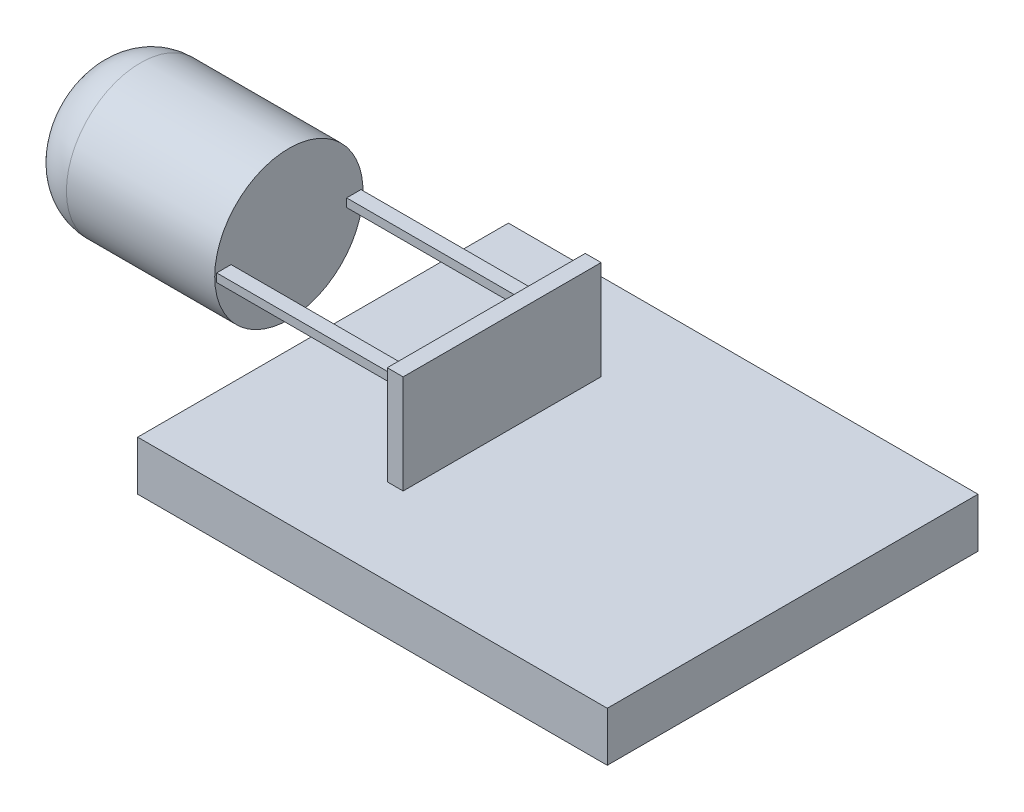
SolidWorks part; units mm, degrees
ref_plane "Plan de face" through (0, 0, 0) normal (0, 0, 1) x (1, 0, 0)
ref_plane "Plan de dessus" through (0, 0, 0) normal (0, 1, 0) x (1, 0, 0)
ref_plane "Plan de droite" through (0, 0, 0) normal (1, 0, 0) x (0, 0, -1)
sketch "Esquisse1" plane through (0, 0, 0) normal (0, 1, 0) x (1, 0, 0)
  line L1 (-9.5, 7.5) -> (9.5, 7.5)
  line L2 (-9.5, 7.5) -> (-9.5, -7.5)
  line L3 (-9.5, -7.5) -> (9.5, -7.5)
  line L4 (9.5, 7.5) -> (9.5, -7.5)
  line L5 (-9.5, 7.5) -> (9.5, -7.5) construction
  line L6 (-9.5, -7.5) -> (9.5, 7.5) construction
  point P0 (0, 0)
  dimension "D1" = 15
  dimension "D2" = 19
extrude "Boss.-Extru.1" add sketch "Esquisse1" along normal blind 2
sketch "Esquisse2" plane through (0, 2, 0) normal (0, 1, 0) x (1, 0, 0)
  line L1 (-2.8834, -4.0184) -> (-2.2409, -4.0184)
  line L2 (-2.8834, -4.0184) -> (-2.8834, 3.9928)
  line L3 (-2.8834, 3.9928) -> (-2.2409, 3.9928)
  line L4 (-2.2409, -4.0184) -> (-2.2409, 3.9928)
extrude "Boss.-Extru.2" add sketch "Esquisse2" along normal blind 4
sketch "Esquisse3" plane through (-2.8834, 0, 0) normal (-1, 0, 0) x (0, 0, 1)
  line L1 (-2.9186, 4.7729) -> (-2.3381, 4.7729)
  line L2 (-2.9186, 4.7729) -> (-2.9186, 4.4343)
  line L3 (-2.9186, 4.4343) -> (-2.3381, 4.4343)
  line L4 (-2.3381, 4.7729) -> (-2.3381, 4.4343)
extrude "Boss.-Extru.3" add sketch "Esquisse3" along normal blind 8
mirror "Symétrie1" about plane through (0, 0, 0) normal (0, 0, 1) of "Boss.-Extru.3"
sketch "Esquisse4" plane through (-10.8834, 0, 0) normal (-1, 0, 0) x (0, 0, 1)
  circle A0 centre (0, 4.6763) radius 3
  dimension "D1" = 6
extrude "Boss.-Extru.4" add sketch "Esquisse4" along normal blind 8
fillet "Congé1" radius 2 1 edges at (-18.8834, 4.6763, 3)
